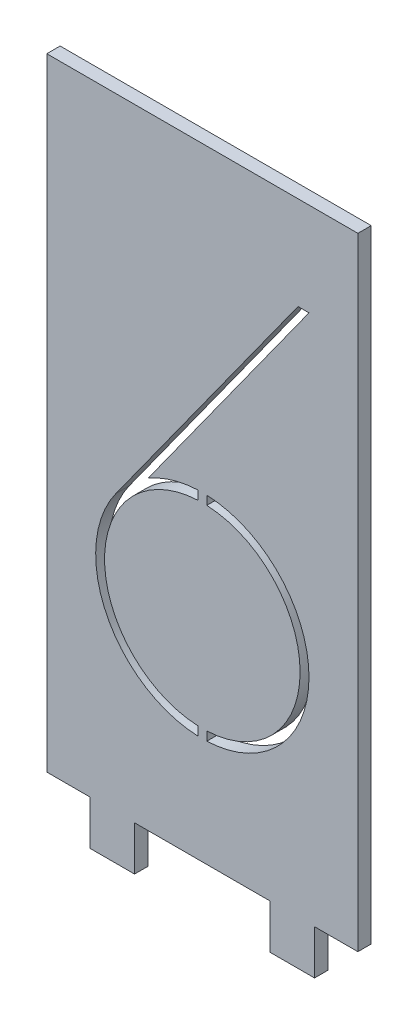
SolidWorks part; units mm, degrees
material "Glas"
ref_plane "Ebene vorne" through (0, 0, 0) normal (0, 0, 1) x (1, 0, 0)
ref_plane "Ebene oben" through (0, 0, 0) normal (0, 1, 0) x (1, 0, 0)
ref_plane "Ebene rechts" through (0, 0, 0) normal (1, 0, 0) x (0, 0, -1)
sketch "Skizze1" plane through (0, 0, 0) normal (0, 0, 1) x (1, 0, 0)
  line L1 (0, 0) -> (35, 0)
  line L2 (0, 0) -> (0, 75)
  line L3 (0, 75) -> (35, 75)
  line L4 (35, 0) -> (35, 75)
  dimension "D1" = 35
  dimension "D2" = 75
extrude "Aufsatz-Linear austragen1" add sketch "Skizze1" along normal blind 1.5
sketch "Skizze3" plane through (0, 0, 1.5) normal (0, 0, 1) x (1, 0, 0)
  line L0 (0, 0) -> (35, 0) construction
  line L1 (9.875, 0) -> (25.125, 0)
  line L2 (9.875, 0) -> (9.875, 5)
  line L3 (9.875, 5) -> (25.125, 5)
  line L4 (25.125, 0) -> (25.125, 5)
  line L5 (35, 0) -> (35, 75) construction
  line L6 (30.125, 5) -> (35, 5)
  line L7 (30.125, 5) -> (30.125, 0)
  line L8 (30.125, 0) -> (35, 0)
  line L9 (35, 5) -> (35, 0)
  line L10 (4.875, 5) -> (0, 5)
  line L11 (4.875, 5) -> (4.875, 0)
  line L12 (4.875, 0) -> (0, 0)
  line L13 (0, 5) -> (0, 0)
  dimension "D1" = 4.875
  dimension "D2" = 4.875
  dimension "D3" = 0
  dimension "D4" = 5
  dimension "D5" = 5
  dimension "D6" = 5
  dimension "D7" = 5
extrude "Schnitt-Linear austragen12" cut sketch "Skizze3" against normal blind 20
sketch "Skizze10" plane through (0, 0, 1.5) normal (0, 0, 1) x (1, 0, 0)
  line L0 (35, 5) -> (35, 75) construction
  line L1 (25.125, 5) -> (9.875, 5) construction
  circle A0 centre (17.5, 29) radius 12
  circle A1 centre (17.5, 29) radius 11
  dimension "D1" = 22
  dimension "D2" = 24
  dimension "D3" = 17.5
  dimension "D4" = 24
extrude "Schnitt-Linear austragen16" cut sketch "Skizze10" against normal blind 1.5
sketch "Skizze11" plane through (0, 0, 1.5) normal (0, 0, 1) x (1, 0, 0)
  line L1 (28.2682, 64.5) -> (29.5, 64.5)
  line L2 (29.5, 64.5) -> (8.288, 35.0116)
  line L6 (35, 75) -> (0, 75) construction
  line L7 (35, 5) -> (35, 75) construction
  line L8 (28.2682, 64.5) -> (7.7874, 36.0474)
  line L9 (7.7874, 36.0474) -> (8.288, 35.0116)
  circle A1 centre (17.5, 29) radius 11 construction
  circle A2 centre (17.5, 29) radius 12 construction
  dimension "D2" = 10.5
  dimension "D3" = 5.5
extrude "Schnitt-Linear austragen17" cut sketch "Skizze11" against normal blind 1.5
sketch "Skizze12" plane through (0, 0, 1.5) normal (0, 0, 1) x (1, 0, 0)
  line L1 (17, 42.6432) -> (18, 42.6432)
  line L2 (17, 42.6432) -> (17, 14.4991)
  line L3 (17, 14.4991) -> (18, 14.4991)
  line L4 (18, 42.6432) -> (18, 14.4991)
  line L5 (35, 5) -> (35, 75) construction
  dimension "D1" = 1
  dimension "D2" = 17
extrude "Aufsatz-Linear austragen7" add sketch "Skizze12" against normal blind 1.5
